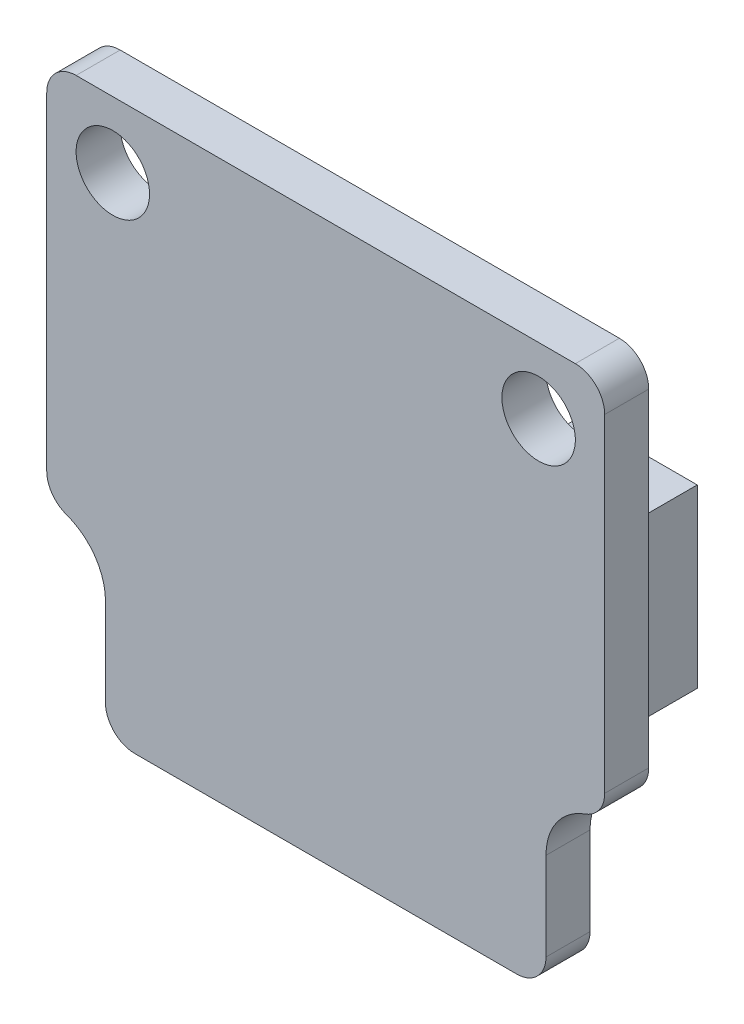
SolidWorks part; units mm, degrees
ref_plane "Front Plane" through (0, 0, 0) normal (0, 0, 1) x (1, 0, 0)
ref_plane "Top Plane" through (0, 0, 0) normal (0, 1, 0) x (1, 0, 0)
ref_plane "Right Plane" through (0, 0, 0) normal (1, 0, 0) x (0, 0, -1)
sketch "Sketch1" plane through (0, 0, 0) normal (0, 0, 1) x (1, 0, 0)
  line L1 (3, 0) -> (16, 0)
  line L2 (0, 6.8284) -> (0, 18)
  line L3 (1, 19) -> (18, 19)
  line L4 (19, 6.8284) -> (19, 18)
  line L5 (2, 4) -> (2, 1)
  line L6 (17, 1) -> (17, 4)
  arc A0 (0.6667, 5.8856) -> (2, 4) centre (0, 4) cw
  arc A1 (17, 4) -> (18.3333, 5.8856) centre (19, 4) cw
  arc A2 (0.6667, 5.8856) -> (0, 6.8284) centre (1, 6.8284) cw
  arc A3 (18.3333, 5.8856) -> (19, 6.8284) centre (18, 6.8284) ccw
  arc A4 (17, 1) -> (16, 0) centre (16, 1) cw
  arc A5 (2, 1) -> (3, 0) centre (3, 1) ccw
  arc A6 (18, 19) -> (19, 18) centre (18, 18) cw
  arc A7 (1, 19) -> (0, 18) centre (1, 18) ccw
  point P14 (19, 6)
  point P21 (19, 19)
  point P24 (0, 19)
  dimension "D3" = 1
  dimension "D1" = 19
  dimension "D2" = 13
  dimension "D4" = 2
  dimension "D5" = 2
extrude "Boss-Extrude1" add sketch "Sketch1" along normal blind 1.5
sketch "Sketch2" plane through (0, 0, 0) normal (0, 0, -1) x (-1, 0, 0)
  line L0 (-19, 6.8284) -> (-19, 18) construction
  line L1 (-18, 19) -> (-1, 19) construction
  circle A0 centre (-16.75, 16.75) radius 1.25
  dimension "D1" = 2.5
  dimension "D3" = 2.25
  dimension "D2" = 2.25
extrude "Cut-Extrude1" cut sketch "Sketch2" against normal through all contours A0
ref_plane "Plane1" through (9.5, 0, 0) normal (-1, 0, 0) x (0, 0, 1)
mirror "Mirror1" about plane through (9.5, 0, 0) normal (-1, 0, 0) of "Cut-Extrude1"
sketch "Sketch3" plane through (0, 0, 0) normal (0, 0, -1) x (-1, 0, 0)
  line L0 (-19, 6.8284) -> (-19, 18) construction
  line L1 (-17.6521, 13) -> (-13.6521, 13)
  line L2 (-17.6521, 13) -> (-17.6521, 7)
  line L3 (-17.6521, 7) -> (-13.6521, 7)
  line L4 (-13.6521, 13) -> (-13.6521, 7)
  line L5 (-18, 19) -> (-1, 19) construction
  line L6 (-3, 0) -> (-16, 0) construction
  dimension "D1" = 1.3479
  dimension "D2" = 6
  dimension "D3" = 7
  dimension "D4" = 4
extrude "Boss-Extrude2" add sketch "Sketch3" along normal blind 3
sketch "Sketch4" plane through (0, 0, 0) normal (0, 0, -1) x (-1, 0, 0)
  text T0 "IMU\r\n"
extrude "Cut-Extrude2" cut sketch "Sketch4" against normal blind 0.5
